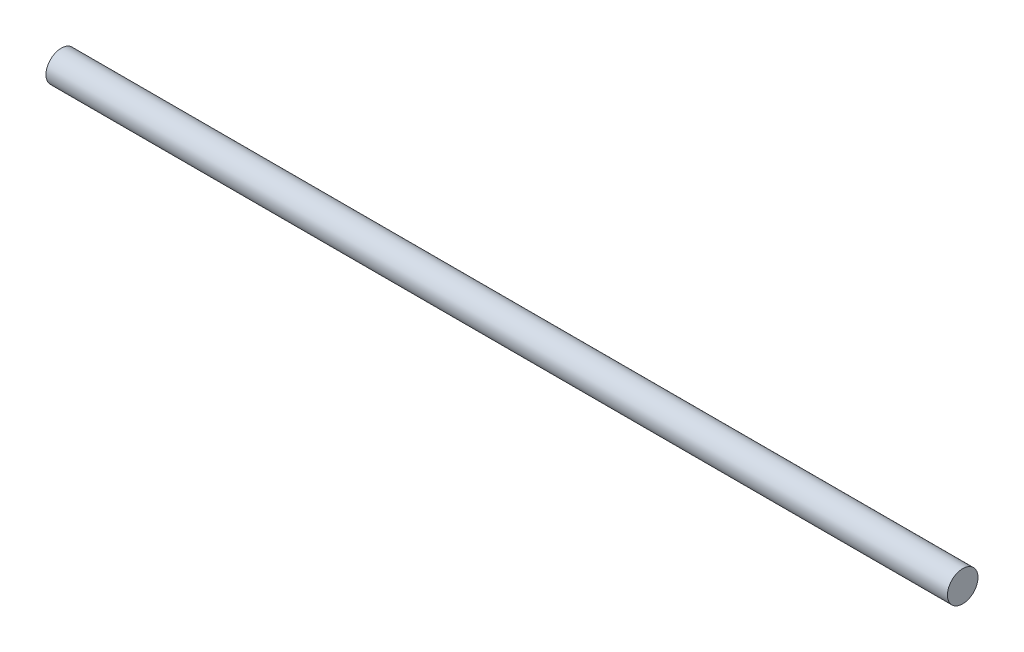
SolidWorks part; units mm, degrees
ref_plane "Front Plane" through (0, 0, 0) normal (0, 0, 1) x (1, 0, 0)
ref_plane "Top Plane" through (0, 0, 0) normal (0, 1, 0) x (1, 0, 0)
ref_plane "Right Plane" through (0, 0, 0) normal (1, 0, 0) x (0, 0, -1)
sketch "Sketch1" plane through (0, 0, 0) normal (1, 0, 0) x (0, 0, -1)
  circle A0 centre (0, 0) radius 10
  dimension "D1" = 20
extrude "Boss-Extrude1" add sketch "Sketch1" along normal blind 590
